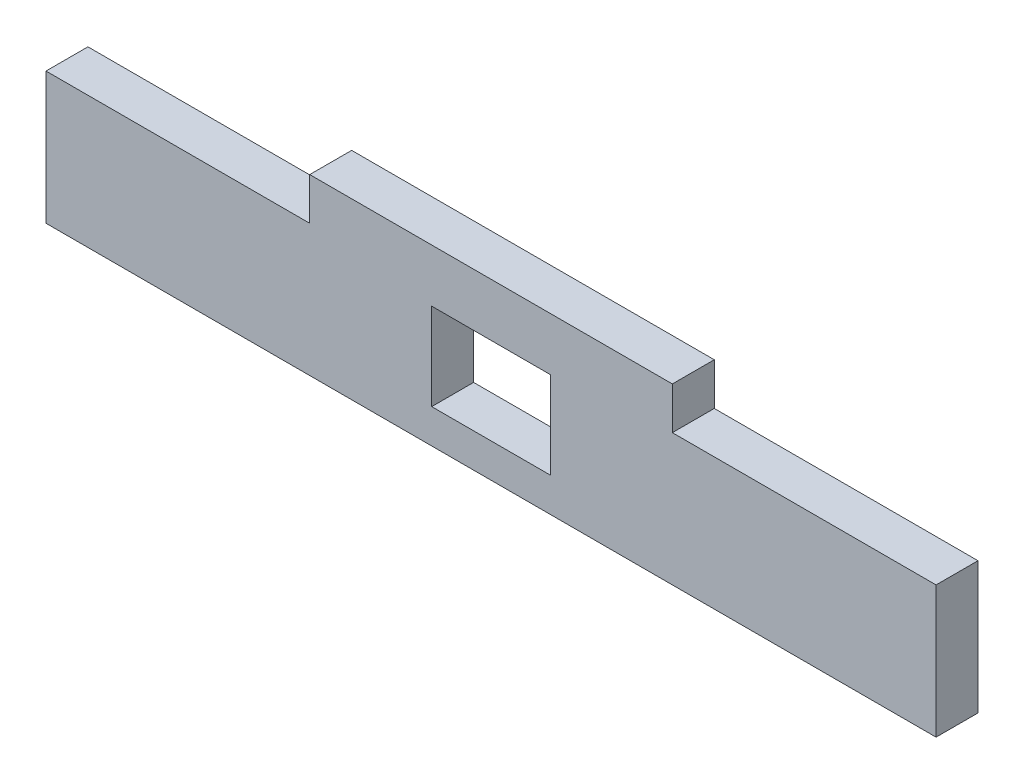
SolidWorks part; units mm, degrees
ref_plane "Front Plane" through (0, 0, 0) normal (0, 0, 1) x (1, 0, 0)
ref_plane "Top Plane" through (0, 0, 0) normal (0, 1, 0) x (1, 0, 0)
ref_plane "Right Plane" through (0, 0, 0) normal (1, 0, 0) x (0, 0, -1)
sketch "Sketch1" plane through (0, 0, 0) normal (0, 0, 1) x (1, 0, 0)
  line L0 (0, 0) -> (85.725, 0)
  line L1 (85.725, 0) -> (85.725, 12.7)
  line L2 (85.725, 12.7) -> (60.325, 12.7)
  line L3 (60.325, 12.7) -> (60.325, 16.764)
  line L4 (60.325, 16.764) -> (25.4, 16.764)
  line L5 (25.4, 16.764) -> (25.4, 12.7)
  line L6 (25.4, 12.7) -> (0, 12.7)
  line L7 (0, 12.7) -> (0, 0)
  line L9 (37.1475, 11.6649) -> (48.5775, 11.6649)
  line L10 (37.1475, 11.6649) -> (37.1475, 3.2829)
  line L11 (37.1475, 3.2829) -> (48.5775, 3.2829)
  line L12 (48.5775, 11.6649) -> (48.5775, 3.2829)
  point P12 (42.8625, 11.6649)
  point P13 (42.8625, 16.764)
extrude "Boss-Extrude1" add sketch "Sketch1" along normal blind 4.0386
